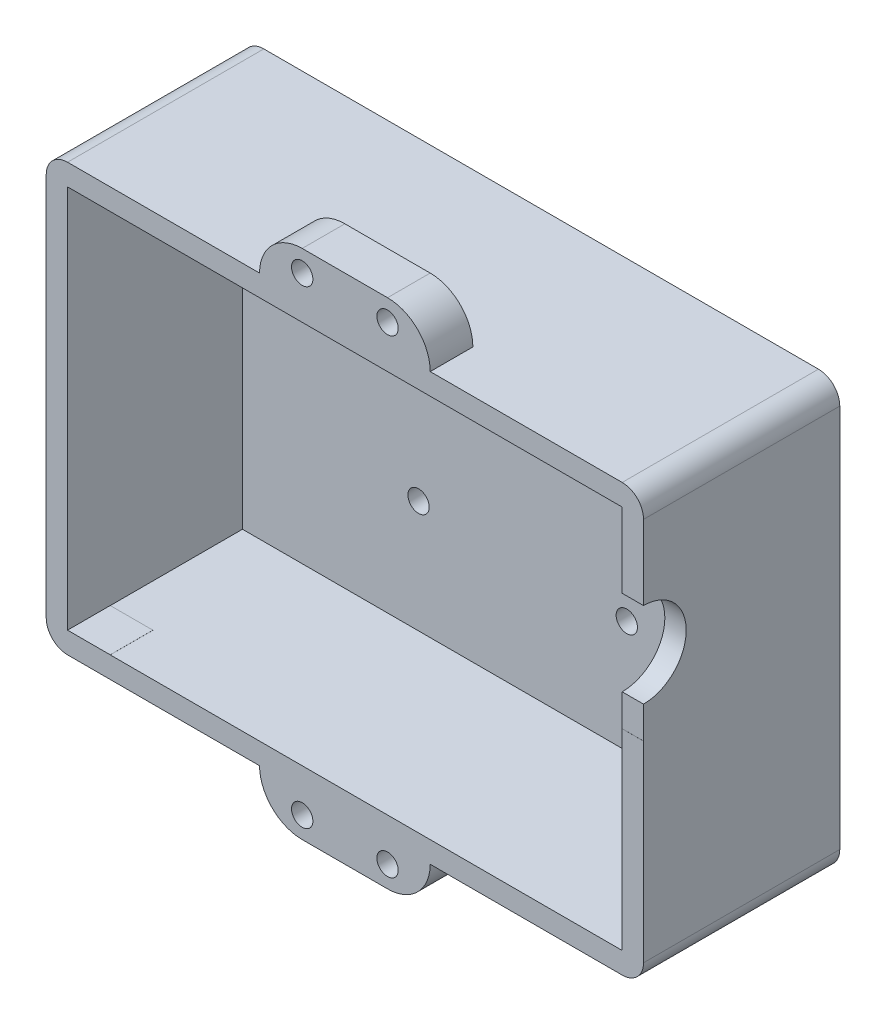
SolidWorks part; units mm, degrees
ref_plane "Front Plane" through (0, 0, 0) normal (0, 0, 1) x (1, 0, 0)
ref_plane "Top Plane" through (0, 0, 0) normal (0, 1, 0) x (1, 0, 0)
ref_plane "Right Plane" through (0, 0, 0) normal (1, 0, 0) x (0, 0, -1)
sketch "Sketch1" plane through (0, 0, 0) normal (0, 0, 1) x (1, 0, 0)
  line L1 (0, 0) -> (76.2, 0)
  line L2 (0, 0) -> (0, -63.5)
  line L3 (0, -63.5) -> (76.2, -63.5)
  line L4 (76.2, 0) -> (76.2, -63.5)
  dimension "D1" = 76.2
  dimension "D2" = 63.5
extrude "Boss-Extrude1" add sketch "Sketch1" along normal blind 31.75
sketch "Sketch2" plane through (0, 0, 31.75) normal (0, 0, 1) x (1, 0, 0)
  line L0 (0, 0) -> (0, -63.5) construction
  line L1 (3.175, -3.175) -> (73.025, -3.175)
  line L2 (3.175, -3.175) -> (3.175, -60.325)
  line L3 (3.175, -60.325) -> (73.025, -60.325)
  line L4 (73.025, -3.175) -> (73.025, -60.325)
  line L5 (76.2, 0) -> (0, 0) construction
  line L6 (76.2, -63.5) -> (76.2, 0) construction
  line L7 (0, -63.5) -> (76.2, -63.5) construction
  dimension "D1" = 3.175
  dimension "D2" = 3.175
  dimension "D3" = 3.175
  dimension "D4" = 3.175
extrude "Cut-Extrude1" cut sketch "Sketch2" against normal blind 28.575
sketch "Sketch3" plane through (0, 0, 0) normal (0, 0, -1) x (-1, 0, 0)
  line L0 (-76.2, 0) -> (0, 0) construction
  line L1 (-47.625, -19.05) -> (-28.575, -19.05)
  line L2 (-47.625, -19.05) -> (-47.625, -44.45)
  line L3 (-47.625, -44.45) -> (-28.575, -44.45)
  line L4 (-28.575, -19.05) -> (-28.575, -44.45)
  line L5 (-76.2, -63.5) -> (-76.2, 0) construction
  point P4 (-38.1, -19.05)
  dimension "D1" = 19.05
  dimension "D2" = 25.4
  dimension "D3" = 19.05
  dimension "D4" = 28.575
extrude "Cut-Extrude2" cut sketch "Sketch3" against normal blind 28.575
sketch "Sketch4" plane through (0, 0, 0) normal (0, 0, -1) x (-1, 0, 0)
  line L0 (-47.625, -19.05) -> (-47.625, -44.45) construction
  line L1 (-28.575, -44.45) -> (-28.575, -19.05) construction
  line L3 (-76.2, 0) -> (0, 0) construction
  line L4 (0, -63.5) -> (-76.2, -63.5) construction
  line L5 (-47.625, -19.05) -> (-47.625, -12.7)
  line L6 (-47.625, -12.7) -> (-28.575, -12.7)
  line L7 (-28.575, -12.7) -> (-28.575, -19.05)
  line L8 (-28.575, -19.05) -> (-47.625, -19.05)
  circle A0 centre (-52.0383, -19.05) radius 1.5875
  circle A1 centre (-24.257, -19.05) radius 1.5875
  circle A2 centre (-52.0382, -44.45) radius 1.5875
  circle A3 centre (-24.257, -44.45) radius 1.5875
  dimension "D1" = 3.175
  dimension "D2" = 27.7812
  dimension "D3" = 4.4132
  dimension "D4" = 4.4132
  dimension "D5" = 27.7812
  dimension "D6" = 4.318
  dimension "D7" = 4.318
  dimension "D8" = 19.05
  dimension "D9" = 19.05
  dimension "D10" = 6.35
extrude "Cut-Extrude3" cut sketch "Sketch4" against normal blind 28.575
sketch "Sketch5" plane through (0, 0, 0) normal (0, 0, -1) x (-1, 0, 0)
  line L0 (-47.625, -44.45) -> (-47.625, -50.8)
  line L1 (-47.625, -50.8) -> (-28.575, -50.8)
  line L2 (-28.575, -50.8) -> (-28.575, -44.45)
  line L3 (-47.625, -44.45) -> (-28.575, -44.45)
  dimension "D1" = 6.35
extrude "Cut-Extrude4" cut sketch "Sketch5" against normal blind 28.575
sketch "Sketch7" plane through (0, 0, 0) normal (0, 1, 0) x (1, 0, 0)
  line L0 (76.2, -31.75) -> (0, -31.75) construction
  line L1 (25.4, -31.75) -> (50.8, -31.75)
  line L2 (25.4, -31.75) -> (25.4, -25.4)
  line L3 (25.4, -25.4) -> (50.8, -25.4)
  line L4 (50.8, -31.75) -> (50.8, -25.4)
  line L5 (0, -31.75) -> (0, 0) construction
  dimension "D1" = 25.4
  dimension "D2" = 6.35
  dimension "D3" = 25.4
extrude "Boss-Extrude2" add sketch "Sketch7" along normal blind 6.35
sketch "Sketch9" plane through (0, 0, 25.4) normal (0, 0, -1) x (-1, 0, 0)
  line L0 (-50.8, 6.35) -> (-50.8, 0) construction
  line L1 (-25.4, 6.35) -> (-25.4, 0) construction
  circle A0 centre (-44.45, 3.175) radius 1.5875
  circle A1 centre (-31.75, 3.175) radius 1.5875
  dimension "D1" = 3.175
  dimension "D2" = 6.35
  dimension "D3" = 6.35
extrude "Cut-Extrude5" cut sketch "Sketch9" against normal blind 6.35
sketch "Sketch10" plane through (0, -63.5, 0) normal (0, -1, 0) x (1, 0, 0)
  line L0 (0, 31.75) -> (76.2, 31.75) construction
  line L1 (25.4, 31.75) -> (50.8, 31.75)
  line L2 (25.4, 31.75) -> (25.4, 25.4)
  line L3 (25.4, 25.4) -> (50.8, 25.4)
  line L4 (50.8, 31.75) -> (50.8, 25.4)
  line L5 (76.2, 31.75) -> (76.2, 0) construction
  dimension "D1" = 25.4
  dimension "D2" = 6.35
  dimension "D3" = 25.4
extrude "Boss-Extrude3" add sketch "Sketch10" along normal blind 6.35
sketch "Sketch11" plane through (0, 0, 25.4) normal (0, 0, -1) x (-1, 0, 0)
  line L0 (-50.8, -69.85) -> (-50.8, -63.5) construction
  line L1 (-25.4, -69.85) -> (-25.4, -63.5) construction
  circle A0 centre (-44.45, -66.675) radius 1.5875
  circle A1 centre (-31.75, -66.675) radius 1.5875
  dimension "D1" = 6.35
  dimension "D2" = 6.35
extrude "Cut-Extrude6" cut sketch "Sketch11" against normal blind 6.35
sketch "Sketch12" plane through (76.2, 0, 0) normal (1, 0, 0) x (0, 0, -1)
  line L1 (-31.75, -63.5) -> (-31.75, 0) construction
  line L2 (-31.75, -63.5) -> (0, -63.5) construction
  circle A1 centre (-31.75, -28.575) radius 6.35
  dimension "D1" = 34.925
  dimension "D2" = 12.7
extrude "Cut-Extrude8" cut sketch "Sketch12" against normal blind 6.35
sketch "Sketch13" plane through (76.2, 0, 0) normal (1, 0, 0) x (0, 0, -1)
  line L1 (-31.75, -22.225) -> (-24.5719, -22.225)
  line L2 (-31.75, -22.225) -> (-31.75, -35.8201)
  line L3 (-31.75, -35.8201) -> (-24.5719, -35.8201)
  line L4 (-24.5719, -22.225) -> (-24.5719, -35.8201)
extrude "Boss-Extrude4" add sketch "Sketch13" against normal blind 3.175
sketch "Sketch14" plane through (76.2, 0, 0) normal (1, 0, 0) x (0, 0, -1)
  line L0 (-31.75, -63.5) -> (-31.75, 0) construction
  line L1 (-25.4, -63.5) -> (-31.75, -63.5) construction
  circle A0 centre (-31.75, -25.4) radius 6.35
  dimension "D1" = 12.7
  dimension "D2" = 38.1
extrude "Cut-Extrude9" cut sketch "Sketch14" against normal blind 3.175
sketch "Sketch15" plane through (0, 0, 0) normal (0, 0, -1) x (-1, 0, 0)
  circle A0 centre (-52.0383, -19.05) radius 1.5875
  circle A1 centre (-24.257, -19.05) radius 1.5875
  circle A2 centre (-24.257, -44.45) radius 1.5875
  circle A3 centre (-52.0382, -44.45) radius 1.5875
sketch "Sketch16" plane through (0, 0, 0) normal (0, 0, -1) x (-1, 0, 0)
  line L0 (-52.0383, -19.05) -> (-52.0383, 0)
  line L1 (-76.2, 0) -> (0, 0) construction
  line L2 (-24.257, -19.05) -> (-24.257, 0)
  line L3 (-52.0382, -44.45) -> (-52.0382, -63.5)
  line L4 (0, -63.5) -> (-76.2, -63.5) construction
  line L5 (-24.257, -44.45) -> (-24.257, -63.5)
  circle A0 centre (-53.6258, -19.05) radius 1.5875
  circle A1 centre (-52.0383, -19.05) radius 1.5875 construction
  circle A2 centre (-53.6257, -44.45) radius 1.5875
  circle A3 centre (-52.0382, -44.45) radius 1.5875 construction
  circle A4 centre (-22.6695, -19.05) radius 1.5875
  circle A5 centre (-24.257, -19.05) radius 1.5875 construction
  circle A6 centre (-22.6695, -44.45) radius 1.5875
  circle A7 centre (-24.257, -44.45) radius 1.5875 construction
  circle M2 centre (-52.0382, -44.45) radius 1.5875
  circle M3 centre (-24.257, -19.05) radius 1.5875
  circle M4 centre (-52.0383, -19.05) radius 1.5875
extrude "Boss-Extrude8" add sketch "Sketch15" against normal blind 3.175
extrude "Cut-Extrude11" cut sketch "Sketch16" against normal blind 8.509 contours A0 M4 | A0 M4 | A4 M3 | A4 M3 | A2 M2 | A2 M2 | A6
sketch "Sketch18" plane through (0, 0, 0) normal (0, 0, -1) x (-1, 0, 0)
  line L0 (-50.1096, -12.7) -> (-47.625, -12.7)
  line L1 (-47.625, -12.7) -> (-26.0904, -12.7)
  line L2 (-47.625, -10.2154) -> (-28.575, -10.2154)
  arc A0 (-47.625, -10.2154) -> (-50.1096, -12.7) centre (-47.625, -12.7) ccw
  arc A1 (-28.575, -10.2154) -> (-26.0904, -12.7) centre (-28.575, -12.7) cw
extrude "Cut-Extrude12" cut sketch "Sketch18" against normal blind 8.509
sketch "Sketch26" plane through (0, 0, 0) normal (0, 0, -1) x (-1, 0, 0)
  line L1 (-76.2, 0) -> (0, 0) construction
  line L2 (0, -63.5) -> (-76.2, -63.5) construction
  line L3 (0, 0) -> (0, -63.5) construction
  line L4 (-76.2, -63.5) -> (-76.2, 0) construction
  circle A0 centre (-68.58, -31.75) radius 2.921
  circle A1 centre (-64.77, -25.4) radius 2.921
  circle A2 centre (-60.96, -19.05) radius 2.921
  circle A3 centre (-64.77, -38.1) radius 2.921
  circle A4 centre (-60.96, -44.45) radius 2.921
  circle A5 centre (-7.62, -31.75) radius 2.921
  circle A6 centre (-11.43, -25.4) radius 2.921
  circle A7 centre (-15.24, -19.05) radius 2.921
  circle A8 centre (-11.43, -38.1) radius 2.921
  circle A9 centre (-15.24, -44.45) radius 2.921
  dimension "D3" = 7.62
  dimension "D4" = 11.43
  dimension "D5" = 15.24
  dimension "D6" = 11.43
  dimension "D7" = 15.24
  dimension "D12" = 7.62
  dimension "D13" = 11.43
  dimension "D14" = 11.43
  dimension "D15" = 15.24
  dimension "D16" = 15.24
  dimension "D17" = 31.75
  dimension "D18" = 25.4
  dimension "D19" = 19.05
  dimension "D20" = 25.4
  dimension "D21" = 19.05
extrude "Cut-Extrude24" cut sketch "Sketch26" against normal blind 72.898
sketch "Sketch32" plane through (0, 0, 3.175) normal (0, 0, 1) x (1, 0, 0)
  line L1 (3.175, -3.175) -> (73.025, -3.175)
  line L2 (3.175, -3.175) -> (3.175, -60.325)
  line L3 (3.175, -60.325) -> (73.025, -60.325)
  line L4 (73.025, -3.175) -> (73.025, -60.325)
  circle A0 centre (15.24, -19.05) radius 2.921
  circle A1 centre (11.43, -25.4) radius 2.921
  circle A2 centre (7.62, -31.75) radius 2.921
  circle A3 centre (11.43, -38.1) radius 2.921
  circle A4 centre (15.24, -44.45) radius 2.921
  circle A5 centre (60.96, -44.45) radius 2.921
  circle A6 centre (64.77, -38.1) radius 2.921
  circle A7 centre (68.58, -31.75) radius 2.921
  circle A8 centre (64.77, -25.4) radius 2.921
  circle A9 centre (60.96, -19.05) radius 2.921
extrude "Boss-Extrude10" add sketch "Sketch32" along normal blind 5.715
sketch "Sketch36" plane through (0, 0, 0) normal (0, 0, -1) x (-1, 0, 0)
  line L1 (-55.2133, -17.4625) -> (-21.082, -17.4625)
  line L2 (-55.2133, -17.4625) -> (-55.2133, -46.0375)
  line L3 (-55.2133, -46.0375) -> (-21.082, -46.0375)
  line L4 (-21.082, -17.4625) -> (-21.082, -46.0375)
extrude "Cut-Extrude27" cut sketch "Sketch36" against normal blind 38.227 contours L2 L1 L4 L3
sketch "Sketch38" plane through (0, 0, 0) normal (0, 0, -1) x (-1, 0, 0)
  line L0 (-55.2133, -46.0375) -> (-21.082, -46.0375)
  spline S0 degree 3 poles (-55.2133, -46.0375) (-46.3247, -54.6455) (-29.9359, -54.7487) (-21.082, -46.0375) knots 0 0 0 0 1 1 1 1
extrude "Cut-Extrude29" cut sketch "Sketch38" against normal blind 38.227
sketch "Sketch39" plane through (0, 0, 8.89) normal (0, 0, 1) x (1, 0, 0)
  line L0 (3.175, -60.325) -> (73.025, -60.325) construction
  line L1 (3.175, -3.175) -> (21.082, -3.175)
  line L2 (3.175, -3.175) -> (3.175, -60.325)
  line L3 (3.175, -60.325) -> (21.082, -60.325)
  line L4 (21.082, -3.175) -> (21.082, -60.325)
  line L6 (73.025, -3.175) -> (55.2132, -3.175)
  line L7 (73.025, -3.175) -> (73.025, -60.325)
  line L8 (73.025, -60.325) -> (55.2132, -60.325)
  line L9 (55.2132, -3.175) -> (55.2132, -60.325)
  circle A0 centre (15.24, -19.05) radius 1.905
  circle A1 centre (11.43, -25.4) radius 1.905
  circle A2 centre (7.62, -31.75) radius 1.905
  circle A3 centre (11.43, -38.1) radius 1.905
  circle A4 centre (15.24, -44.45) radius 1.905
  circle A5 centre (60.96, -44.45) radius 1.905
  circle A6 centre (64.77, -38.1) radius 1.905
  circle A7 centre (68.58, -31.75) radius 1.905
  circle A8 centre (64.77, -25.4) radius 1.905
  circle A9 centre (60.96, -19.05) radius 1.905
  dimension "D1" = 3.81
extrude "Boss-Extrude11" add sketch "Sketch39" along normal blind 2.54
sketch "Sketch44" plane through (0, 0, 0) normal (0, 0, -1) x (-1, 0, 0)
  line L0 (-28.575, -12.7) -> (-28.575, -17.4625) construction
  line L1 (-28.575, -17.4625) -> (-47.625, -17.4625) construction
  line L2 (-47.625, -9.8743) -> (-28.575, -9.9695)
  line L3 (-21.082, -17.4625) -> (-55.2133, -17.4625)
  arc A0 (-55.2133, -17.4625) -> (-47.625, -9.8743) centre (-47.625, -17.4625) cw
  arc A1 (-21.082, -17.4625) -> (-28.575, -9.9695) centre (-28.575, -17.4625) ccw
extrude "Cut-Extrude34" cut sketch "Sketch44" against normal blind 11.176
sketch "Sketch47" plane through (0, 0, 0) normal (0, 0, -1) x (-1, 0, 0)
  line L0 (-76.2, 0) -> (0, 0) construction
  line L1 (-55.372, -9.144) -> (-20.828, -9.144)
  line L2 (-55.372, -9.144) -> (-55.372, -54.356)
  line L3 (-55.372, -54.356) -> (-20.828, -54.356)
  line L4 (-20.828, -9.144) -> (-20.828, -54.356)
  line L5 (-76.2, -63.5) -> (-76.2, 0) construction
  line L6 (-44.0174, -9.144) -> (-55.372, -9.144)
  line L7 (-55.372, -44.45) -> (-55.372, -54.356)
  line L8 (-32.3914, -54.356) -> (-20.828, -54.356)
  line L9 (-32.3914, -9.144) -> (-20.828, -9.144)
  spline S0 degree 2 poles (-55.372, -19.05) (-51.6624, -8.9987) (-44.0174, -9.144) knots 0 0 0 1 1 1
  spline S1 degree 2 poles (-20.828, -19.05) (-24.615, -8.9285) (-32.3914, -9.144) knots 0 0 0 1 1 1
  spline S2 degree 2 poles (-55.372, -44.45) (-51.6624, -54.5013) (-44.0174, -54.356) knots 0 0 0 1 1 1
  spline S3 degree 2 poles (-20.828, -44.45) (-24.615, -54.5715) (-32.3914, -54.356) knots 0 0 0 1 1 1
  point P4 (-55.372, -31.75)
  point P7 (-38.1, -9.144)
  dimension "D1" = 34.544
  dimension "D2" = 45.212
  dimension "D3" = 31.75
  dimension "D4" = 38.1
extrude "Cut-Extrude36" cut sketch "Sketch47" against normal blind 11.43 contours L2 L1 L4 L3
sketch "Sketch51" plane through (76.2, 0, 0) normal (1, 0, 0) x (0, 0, -1)
  line L1 (0, 0) -> (-31.75, 0)
  line L2 (0, 0) -> (0, -63.5)
  line L3 (0, -63.5) -> (-31.75, -63.5)
  line L4 (-31.75, 0) -> (-31.75, -63.5)
extrude "Boss-Extrude16" add sketch "Sketch51" along normal blind 6.35
sketch "Sketch52" plane through (0, 0, 0) normal (-1, 0, 0) x (0, 0, 1)
  line L1 (0, 0) -> (31.75, 0)
  line L2 (0, 0) -> (0, -63.5)
  line L3 (0, -63.5) -> (31.75, -63.5)
  line L4 (31.75, 0) -> (31.75, -63.5)
extrude "Boss-Extrude17" add sketch "Sketch52" along normal blind 6.35
sketch "Sketch53" plane through (76.2, 0, 0) normal (-1, 0, 0) x (0, 0, 1)
  line L0 (31.75, -19.05) -> (31.75, -31.75) construction
  circle A0 centre (31.75, -25.4) radius 6.35
extrude "Cut-Extrude37" cut sketch "Sketch53" against normal blind 6.35
sketch "Sketch54" plane through (0, 0, 31.75) normal (0, 0, 1) x (1, 0, 0)
  line L1 (3.175, -3.175) -> (-3.175, -3.175)
  line L2 (3.175, -3.175) -> (3.175, -60.1885)
  line L3 (3.175, -60.1885) -> (-3.175, -60.1885)
  line L4 (-3.175, -3.175) -> (-3.175, -60.1885)
  line L5 (73.025, -3.175) -> (79.375, -3.175)
  line L6 (73.025, -3.175) -> (73.025, -60.325)
  line L7 (73.025, -60.325) -> (79.375, -60.325)
  line L8 (79.375, -3.175) -> (79.375, -60.325)
  dimension "D1" = 6.35
  dimension "D2" = 6.35
extrude "Cut-Extrude38" cut sketch "Sketch54" against normal blind 21.59
sketch "Sketch57" plane through (0, 0, 10.16) normal (0, 0, 1) x (1, 0, 0)
  line L1 (-3.175, -3.175) -> (3.175, -3.175)
  line L2 (-3.175, -3.175) -> (-3.175, -60.325)
  line L3 (-3.175, -60.325) -> (3.175, -60.325)
  line L4 (3.175, -3.175) -> (3.175, -60.325)
  line L5 (73.025, -60.325) -> (79.375, -60.325)
  line L6 (73.025, -60.325) -> (73.025, -3.175)
  line L7 (73.025, -3.175) -> (79.375, -3.175)
  line L8 (79.375, -60.325) -> (79.375, -3.175)
extrude "Boss-Extrude20" add sketch "Sketch57" along normal blind 1.27
sketch "Sketch59" plane through (0, 0, 0) normal (0, 0, -1) x (-1, 0, 0)
  line L1 (-56.5485, -13.4059) -> (-73.3958, -13.4059)
  line L2 (-56.5485, -13.4059) -> (-56.5485, -49.4675)
  line L3 (-56.5485, -49.4675) -> (-73.3958, -49.4675)
  line L4 (-73.3958, -13.4059) -> (-73.3958, -49.4675)
  line L5 (-19.1642, -12.2921) -> (-2.4561, -12.2921)
  line L6 (-19.1642, -12.2921) -> (-19.1642, -48.9106)
  line L7 (-19.1642, -48.9106) -> (-2.4561, -48.9106)
  line L8 (-2.4561, -12.2921) -> (-2.4561, -48.9106)
extrude "Boss-Extrude21" add sketch "Sketch59" against normal blind 11.43
sketch "Sketch61" plane through (0, 0, 0) normal (0, 0, -1) x (-1, 0, 0)
  line L0 (-82.55, -63.5) -> (-82.55, 0) construction
  line L1 (-82.55, 0) -> (6.35, 0) construction
  line L2 (6.35, -63.5) -> (-82.55, -63.5) construction
  line L3 (6.35, 0) -> (6.35, -63.5) construction
  circle A0 centre (-74.93, -31.75) radius 2.921
  circle A1 centre (-71.12, -25.4) radius 2.921
  circle A2 centre (73.7439, -27.6774) radius 2.921
  circle A3 centre (-67.31, -19.05) radius 2.921
  circle A4 centre (-71.12, -38.1) radius 2.921
  circle A5 centre (-67.31, -44.45) radius 2.921
  circle A6 centre (-1.27, -31.75) radius 2.921
  circle A7 centre (-5.08, -25.4) radius 2.921
  circle A8 centre (-8.89, -19.05) radius 2.921
  circle A9 centre (-5.08, -38.1) radius 2.921
  circle A10 centre (-8.89, -44.45) radius 2.921
  dimension "D1" = 7.62
  dimension "D2" = 11.43
  dimension "D3" = 11.43
  dimension "D4" = 15.24
  dimension "D5" = 15.24
  dimension "D6" = 31.75
  dimension "D7" = 25.4
  dimension "D8" = 25.4
  dimension "D9" = 19.05
  dimension "D10" = 19.05
  dimension "D11" = 7.62
  dimension "D12" = 31.75
  dimension "D13" = 11.43
  dimension "D14" = 25.4
  dimension "D15" = 19.05
  dimension "D16" = 15.24
  dimension "D17" = 11.43
  dimension "D18" = 25.4
  dimension "D19" = 15.24
  dimension "D20" = 19.05
extrude "Cut-Extrude39" cut sketch "Sketch61" against normal blind 8.89
sketch "Sketch62" plane through (0, 0, 8.89) normal (0, 0, -1) x (-1, 0, 0)
  circle A0 centre (-67.31, -19.05) radius 1.905
  circle A1 centre (-71.12, -25.4) radius 1.905
  circle A2 centre (-74.93, -31.75) radius 1.905
  circle A3 centre (-71.12, -38.1) radius 1.905
  circle A4 centre (-67.31, -44.45) radius 1.905
  circle A5 centre (-8.89, -44.45) radius 1.905
  circle A6 centre (-5.08, -38.1) radius 1.905
  circle A7 centre (-1.27, -31.75) radius 1.905
  circle A8 centre (-5.08, -25.4) radius 1.905
  circle A9 centre (-8.89, -19.05) radius 1.905
  dimension "D1" = 3.81
extrude "Cut-Extrude40" cut sketch "Sketch62" against normal blind 2.54
sketch "Sketch63" plane through (-3.175, 0, 0) normal (1, 0, 0) x (0, 0, -1)
  line L6 (-11.43, -3.175) -> (-31.75, -3.175) construction
  line L7 (-20.32, -3.175) -> (-21.59, -3.175)
  line L8 (-20.32, -3.175) -> (-20.32, -60.1885)
  line L9 (-20.32, -60.1885) -> (-21.59, -60.1885)
  line L10 (-21.59, -3.175) -> (-21.59, -60.1885)
  line L11 (-11.43, -60.1885) -> (-31.75, -60.1885) construction
  line L12 (-11.43, -3.175) -> (-11.43, -60.1885) construction
  line L14 (-21.59, -3.175) -> (-25.4, -3.175)
  line L15 (-21.59, -3.175) -> (-21.59, -60.1885)
  line L16 (-21.59, -60.1885) -> (-25.4, -60.1885)
  line L17 (-25.4, -3.175) -> (-25.4, -60.1885)
  dimension "D1" = 8.89
  dimension "D2" = 1.27
  dimension "D3" = 3.81
sketch "Sketch64" plane through (0, -60.1885, 0) normal (0, 1, 0) x (1, 0, 0)
  line L1 (-3.175, -11.43) -> (3.175, -11.43)
  line L2 (-3.175, -11.43) -> (-3.175, -31.75)
  line L3 (-3.175, -31.75) -> (3.175, -31.75)
  line L4 (3.175, -11.43) -> (3.175, -31.75)
extrude "Cut-Extrude42" cut sketch "Sketch64" against normal blind 0.127
extrude "Boss-Extrude22" add sketch "Sketch63" along normal blind 83.439 contours L8 L7 L10 L9 | L15 L14 L17 L16
sketch "Sketch65" plane through (0, 0, 0) normal (0, 0, -1) x (-1, 0, 0)
  line L0 (-82.55, 0) -> (6.35, 0) construction
  line L1 (6.35, 0) -> (6.35, -63.5) construction
  line L2 (-82.55, -63.5) -> (-82.55, 0) construction
  circle A0 centre (-53.594, -19.05) radius 1.5875
  circle A1 centre (-22.606, -19.05) radius 1.5875
  circle A2 centre (-22.606, -44.45) radius 1.5875
  circle A3 centre (-53.594, -44.45) radius 1.5875
  dimension "D1" = 3.175
  dimension "D2" = 25.4
  dimension "D3" = 25.4
  dimension "D4" = 19.05
  dimension "D5" = 19.05
  dimension "D6" = 28.956
  dimension "D7" = 28.956
  dimension "D8" = 28.956
  dimension "D9" = 28.956
extrude "Cut-Extrude43" cut sketch "Sketch65" against normal blind 83.439
sketch "Sketch66" plane through (0, 0, 20.32) normal (0, 0, -1) x (-1, 0, 0)
  line L0 (-82.55, -63.5) -> (-82.55, 0) construction
  line L1 (-50.8, -12.7) -> (-25.4, -12.7)
  line L2 (-50.8, -12.7) -> (-50.8, -50.8)
  line L3 (-50.8, -50.8) -> (-25.4, -50.8)
  line L4 (-25.4, -12.7) -> (-25.4, -50.8)
  line L5 (-82.55, 0) -> (6.35, 0) construction
  point P4 (-50.8, -31.75)
  point P6 (-38.1, -12.7)
  dimension "D3" = 44.45
  dimension "D1" = 25.4
  dimension "D2" = 38.1
  dimension "D4" = 31.75
extrude "Cut-Extrude44" cut sketch "Sketch66" against normal blind 83.439
sketch "Sketch67" plane through (0, 0, 0) normal (0, 0, -1) x (-1, 0, 0)
  line L0 (-55.372, -9.144) -> (-55.372, -54.356) construction
  line L1 (-55.372, -9.144) -> (-20.828, -9.144) construction
  line L2 (-20.828, -9.144) -> (-20.828, -54.356) construction
  line L3 (-55.372, -54.356) -> (-20.828, -54.356) construction
  line L4 (-53.6737, -9.144) -> (-55.372, -9.144)
  line L5 (-55.372, -9.144) -> (-55.372, -12.7)
  line L6 (-55.372, -50.8) -> (-55.372, -54.356)
  line L7 (-55.372, -54.356) -> (-53.6737, -54.356)
  line L8 (-22.5263, -54.356) -> (-20.828, -54.356)
  line L9 (-20.828, -54.356) -> (-20.828, -50.8)
  line L10 (-20.828, -12.7) -> (-20.828, -9.144)
  line L11 (-20.828, -9.144) -> (-22.5263, -9.144)
  arc A0 (-55.372, -12.7) -> (-53.6737, -9.144) centre (-50.8, -12.7) cw
  arc A1 (-20.828, -12.7) -> (-22.5263, -9.144) centre (-25.4, -12.7) ccw
  arc A2 (-20.828, -50.8) -> (-22.5263, -54.356) centre (-25.4, -50.8) cw
  arc A3 (-55.372, -50.8) -> (-53.6737, -54.356) centre (-50.8, -50.8) ccw
extrude "Boss-Extrude23" add sketch "Sketch67" against normal blind 11.43
sketch "Sketch68" plane through (0, 0, 20.32) normal (0, 0, -1) x (-1, 0, 0)
  line L0 (-67.31, -17.145) -> (-65.405, -19.05)
  line L1 (-65.405, -19.05) -> (-73.025, -31.75)
  line L2 (-73.025, -31.75) -> (-65.405, -44.45)
  line L3 (-65.405, -44.45) -> (-67.31, -46.355)
  line L4 (-67.31, -46.355) -> (-76.835, -31.75)
  line L5 (-76.835, -31.75) -> (-67.31, -17.145)
  line L6 (-10.795, -19.05) -> (-8.89, -17.145)
  line L7 (-8.89, -17.145) -> (0.635, -31.75)
  line L8 (0.635, -31.75) -> (-8.89, -46.355)
  line L9 (-8.89, -46.355) -> (-10.795, -44.45)
  line L10 (-10.795, -44.45) -> (-3.175, -31.75)
  line L11 (-3.175, -31.75) -> (-10.795, -19.05)
  circle A0 centre (-67.31, -19.05) radius 1.905 construction
  circle A1 centre (-74.93, -31.75) radius 1.905 construction
  circle A2 centre (-67.31, -44.45) radius 1.905 construction
  circle A3 centre (-8.89, -19.05) radius 1.905 construction
  circle A4 centre (-1.27, -31.75) radius 1.905 construction
  circle A5 centre (-8.89, -44.45) radius 1.905 construction
extrude "Cut-Extrude45" cut sketch "Sketch68" against normal blind 11.43
sketch "Sketch71" plane through (0, 0, 31.75) normal (0, 0, 1) x (1, 0, 0)
  line L0 (25.4, 0) -> (-6.35, 0) construction
  line L1 (-6.35, -63.5) -> (-6.35, 0) construction
  line L2 (82.55, 0) -> (50.8, 0) construction
  line L3 (82.55, 0) -> (82.55, -19.05) construction
  line L4 (82.55, -31.75) -> (82.55, -63.5) construction
  line L5 (50.8, -63.5) -> (82.55, -63.5) construction
  line L6 (-3.175, 0) -> (-6.35, 0)
  line L7 (-6.35, 0) -> (-6.35, -3.175)
  line L8 (-6.35, -60.3155) -> (-6.35, -63.5)
  line L9 (-6.35, -63.5) -> (-3.175, -63.4905)
  line L10 (82.55, -60.325) -> (82.55, -63.5)
  line L11 (82.55, -63.5) -> (79.375, -63.5)
  line L12 (79.375, 0) -> (82.55, 0)
  line L13 (82.55, 0) -> (82.55, -3.175)
  arc A0 (-3.175, 0) -> (-6.35, -3.175) centre (-3.175, -3.175) ccw
  arc A1 (79.375, 0) -> (82.55, -3.175) centre (79.375, -3.175) cw
  arc A2 (82.55, -60.325) -> (79.375, -63.5) centre (79.375, -60.325) cw
  arc A3 (-6.35, -60.3155) -> (-3.175, -63.4905) centre (-3.175, -60.3155) ccw
extrude "Cut-Extrude47" cut sketch "Sketch71" against normal blind 63.5
sketch "Sketch72" plane through (-3.175, 0, 0) normal (1, 0, 0) x (0, 0, -1)
  circle A0 centre (-31.75, -25.4) radius 6.35
extrude "Cut-Extrude48" cut sketch "Sketch72" against normal blind 63.5
sketch "Sketch73" plane through (82.55, 0, 0) normal (1, 0, 0) x (0, 0, -1)
  line L0 (-31.75, -3.175) -> (-31.75, -19.05) construction
  line L1 (-31.75, -19.05) -> (-23.8556, -19.05)
  line L2 (-31.75, -19.05) -> (-31.75, -31.75)
  line L3 (-31.75, -31.75) -> (-23.8556, -31.75)
  line L4 (-23.8556, -19.05) -> (-23.8556, -31.75)
  arc A0 (-31.75, -31.75) -> (-31.75, -19.05) centre (-31.75, -25.4) ccw construction
extrude "Boss-Extrude24" add sketch "Sketch73" against normal blind 3.175
sketch "Sketch74" plane through (0, 0, 25.4) normal (0, 0, -1) x (-1, 0, 0)
  line L0 (-50.8, 0) -> (-25.4, 0) construction
  line L5 (-44.45, 6.35) -> (-50.8, 6.35)
  line L10 (-50.8, 6.35) -> (-50.8, 0)
  line L11 (-31.75, 6.35) -> (-25.4, 6.35)
  line L12 (-25.4, 6.35) -> (-25.4, 0)
  arc A0 (-44.45, 6.35) -> (-50.8, 0) centre (-44.45, 0) ccw
  arc A1 (-31.75, 6.35) -> (-25.4, 0) centre (-31.75, 0) cw
extrude "Cut-Extrude49" cut sketch "Sketch74" against normal blind 9.779
sketch "Sketch75" plane through (0, 0, 25.4) normal (0, 0, -1) x (-1, 0, 0)
  line L0 (6.35, -63.5) -> (-79.375, -63.5) construction
  line L5 (-25.4, -63.5) -> (-50.8, -63.5) construction
  line L10 (-50.8, -63.5) -> (-50.8, -69.85)
  line L11 (-50.8, -69.85) -> (-44.45, -69.85)
  line L12 (-31.75, -69.85) -> (-25.4, -69.85)
  line L13 (-25.4, -69.85) -> (-25.4, -63.5)
  arc A0 (-50.8, -63.5) -> (-44.45, -69.85) centre (-44.45, -63.5) ccw
  arc A1 (-25.4, -63.5) -> (-31.75, -69.85) centre (-31.75, -63.5) cw
  dimension "D1" = 6.35
  dimension "D2" = 6.35
extrude "Cut-Extrude50" cut sketch "Sketch75" against normal blind 9.779
sketch "Sketch76" plane through (0, 0, 20.32) normal (0, 0, -1) x (-1, 0, 0)
  line L0 (-67.31, -16.129) -> (-64.389, -19.05)
  line L1 (-64.389, -19.05) -> (-72.009, -31.75)
  line L2 (-72.009, -31.75) -> (-64.389, -44.45)
  line L3 (-64.389, -44.45) -> (-67.31, -47.371)
  line L4 (-67.31, -47.371) -> (-77.851, -31.75)
  line L5 (-77.851, -31.75) -> (-67.31, -16.129)
  line L6 (-11.811, -19.05) -> (-8.89, -16.129)
  line L7 (-8.89, -16.129) -> (1.651, -31.75)
  line L8 (1.651, -31.75) -> (-7.5154, -47.0274)
  line L9 (-7.5154, -47.0274) -> (-11.811, -44.45)
  line L10 (-11.811, -44.45) -> (-4.191, -31.75)
  line L11 (-4.191, -31.75) -> (-11.811, -19.05)
  circle A0 centre (-67.31, -19.05) radius 2.921 construction
  circle A1 centre (-67.31, -19.05) radius 2.921 construction
  circle A2 centre (-74.93, -31.75) radius 2.921 construction
  circle A3 centre (-74.93, -31.75) radius 2.921 construction
  circle A4 centre (-67.31, -44.45) radius 2.921 construction
  circle A5 centre (-67.31, -44.45) radius 2.921 construction
  circle A6 centre (-8.89, -19.05) radius 2.921 construction
  circle A7 centre (-8.89, -19.05) radius 2.921 construction
  circle A8 centre (-1.27, -31.75) radius 2.921 construction
  circle A9 centre (-1.27, -31.75) radius 2.921 construction
  circle A10 centre (-8.89, -44.45) radius 2.921 construction
  circle A11 centre (-8.89, -44.45) radius 2.921 construction
extrude "Cut-Extrude51" cut sketch "Sketch76" against normal blind 9.779
sketch "Sketch81" plane through (0, 0, 31.75) normal (0, 0, 1) x (1, 0, 0)
  line L1 (-3.175, -63.4905) -> (-6.4183, -63.4905)
  line L2 (-3.175, -63.4905) -> (-3.175, -63.525)
  line L3 (-3.175, -63.525) -> (-6.4183, -63.525)
  line L4 (-6.4183, -63.4905) -> (-6.4183, -63.525)
extrude "Cut-Extrude52" cut sketch "Sketch81" against normal blind 36.703
sketch "Sketch85" plane through (0, 0, 0) normal (0, 0, -1) x (-1, 0, 0)
  circle A0 centre (-67.31, -19.05) radius 2.921
  circle A1 centre (-71.12, -25.4) radius 2.921
  circle A2 centre (-74.93, -31.75) radius 2.921
  circle A3 centre (-71.12, -38.1) radius 2.921
  circle A4 centre (-67.31, -44.45) radius 2.921
  circle A5 centre (-8.89, -44.45) radius 2.921
  circle A6 centre (-5.08, -38.1) radius 2.921
  circle A7 centre (-1.27, -31.75) radius 2.921
  circle A8 centre (-5.08, -25.4) radius 2.921
  circle A9 centre (-8.89, -19.05) radius 2.921
extrude "Cut-Extrude53" cut sketch "Sketch85" against normal blind 11.43
sketch "Sketch86" plane through (0, 0, 11.43) normal (0, 0, 1) x (1, 0, 0)
  line L1 (-3.175, -3.175) -> (79.375, -3.175)
  line L2 (-3.175, -3.175) -> (-3.175, -60.325)
  line L3 (-3.175, -60.325) -> (79.375, -60.325)
  line L4 (79.375, -3.175) -> (79.375, -60.325)
  circle A0 centre (5.08, -25.4) radius 1.905
  circle A1 centre (8.89, -19.05) radius 1.905
  circle A2 centre (1.27, -31.75) radius 1.905
  circle A3 centre (5.08, -38.1) radius 1.905
  circle A4 centre (8.89, -44.45) radius 1.905
  circle A5 centre (67.31, -19.05) radius 1.905
  circle A6 centre (71.12, -25.4) radius 1.905
  circle A7 centre (74.93, -31.75) radius 1.905
  circle A8 centre (71.12, -38.1) radius 1.905
  circle A9 centre (67.31, -44.45) radius 1.905
  dimension "D1" = 3.81
extrude "Boss-Extrude28" add sketch "Sketch86" along normal blind 2.54
sketch "Sketch87" plane through (0, 0, 25.4) normal (0, 0, 1) x (1, 0, 0)
  line L0 (25.4, -12.7) -> (50.8, -12.7) construction
  line L1 (25.4698, -12.7) -> (50.8, -12.7)
  line L2 (25.4698, -12.7) -> (25.4698, -50.8)
  line L3 (25.4698, -50.8) -> (50.8, -50.8)
  line L4 (50.8, -12.7) -> (50.8, -50.8)
  circle A0 centre (22.606, -19.05) radius 1.5875
  circle A1 centre (53.594, -19.05) radius 1.5875
  circle A2 centre (53.594, -44.45) radius 1.5875
  circle A3 centre (22.606, -44.45) radius 1.5875
extrude "Cut-Extrude54" cut sketch "Sketch87" against normal blind 38.862
sketch "Sketch88" plane through (0, 0, 11.43) normal (0, 0, -1) x (-1, 0, 0)
  line L1 (-55.372, -12.7) -> (-20.828, -12.7)
  line L2 (-55.372, -12.7) -> (-55.372, -50.8)
  line L3 (-55.372, -50.8) -> (-20.828, -50.8)
  line L4 (-20.828, -12.7) -> (-20.828, -50.8)
  line L5 (-53.6737, -9.144) -> (-22.5263, -9.144)
  line L6 (-53.6737, -9.144) -> (-53.6737, -12.7)
  line L7 (-53.6737, -12.7) -> (-22.5263, -12.7)
  line L8 (-22.5263, -9.144) -> (-22.5263, -12.7)
  line L9 (-53.6737, -54.356) -> (-22.5263, -54.356)
  line L10 (-53.6737, -54.356) -> (-53.6737, -50.8)
  line L11 (-53.6737, -50.8) -> (-22.5263, -50.8)
  line L12 (-22.5263, -54.356) -> (-22.5263, -50.8)
  arc A0 (-55.372, -12.7) -> (-53.6737, -9.144) centre (-50.8, -12.7) cw
  arc A1 (-20.828, -12.7) -> (-22.4774, -9.1515) centre (-25.4698, -12.7) ccw
  arc A2 (-20.828, -50.8) -> (-22.5529, -54.4108) centre (-25.4698, -50.8) cw
  arc A3 (-55.372, -50.8) -> (-53.6737, -54.356) centre (-50.8, -50.8) ccw
  arc A4 (-55.372, -50.8) -> (-53.6737, -54.356) centre (-50.8, -50.8) ccw construction
extrude "Cut-Extrude55" cut sketch "Sketch88" against normal blind 2.54 contours L6 L5 L8 L7 | L2 L1 L4 L3 | L10 L9 L12 L11
sketch "Sketch89" plane through (0, 0, 11.43) normal (0, 0, -1) x (-1, 0, 0)
  line L0 (-53.6737, -9.144) -> (-53.6737, -12.7) construction
  line L1 (-53.6737, -9.144) -> (-22.5263, -9.144)
  line L2 (-20.828, -50.8) -> (-20.828, -12.7)
  line L3 (-55.372, -12.7) -> (-55.372, -50.8)
  line L4 (-53.6737, -54.356) -> (-22.5263, -54.356)
  arc A0 (-55.372, -12.7) -> (-53.6737, -9.144) centre (-50.8, -12.7) cw
  arc A1 (-20.828, -12.7) -> (-22.5263, -9.144) centre (-25.4, -12.7) ccw
  arc A2 (-20.828, -12.7) -> (-22.5263, -9.144) centre (-25.4, -12.7) ccw construction
  arc A3 (-20.828, -50.8) -> (-22.5263, -54.356) centre (-25.4, -50.8) cw
  arc A4 (-22.5263, -54.356) -> (-20.828, -50.8) centre (-25.4, -50.8) ccw construction
  arc A5 (-55.372, -50.8) -> (-53.6737, -54.356) centre (-50.8, -50.8) ccw
  arc A6 (-55.372, -50.8) -> (-53.6737, -54.356) centre (-50.8, -50.8) ccw construction
extrude "Cut-Extrude56" cut sketch "Sketch89" against normal blind 2.54
sketch "Sketch90" plane through (0, 0, 0) normal (0, 0, -1) x (-1, 0, 0)
  line L0 (-80.8542, -31.75) -> (-67.7643, -9.9334)
  line L1 (-80.8542, -31.75) -> (-67.422, -54.1371)
  line L2 (-67.7643, -9.9334) -> (-59.0521, -15.1607)
  line L3 (-67.422, -54.1371) -> (-58.7098, -48.9099)
  line L4 (-58.7098, -48.9099) -> (-69.0058, -31.75)
  line L5 (-69.0058, -31.75) -> (-59.0521, -15.1607)
  line L6 (-8.4868, -9.8483) -> (4.6542, -31.75)
  line L7 (-17.1565, -15.1462) -> (-7.1942, -31.75)
  line L8 (4.6542, -31.75) -> (-8.7009, -54.0086)
  line L9 (-7.1942, -31.75) -> (-17.225, -48.4679)
  line L10 (-8.4868, -9.8483) -> (-17.1565, -15.1462)
  line L11 (-17.225, -48.4679) -> (-8.7009, -54.0086)
  circle A2 centre (-67.31, -19.05) radius 2.921 construction
  circle A4 centre (-71.12, -25.4) radius 2.921 construction
  circle A5 centre (-74.93, -31.75) radius 2.921 construction
  circle A6 centre (-71.12, -38.1) radius 2.921 construction
  circle A7 centre (-67.31, -44.45) radius 2.921 construction
  circle A8 centre (-1.27, -31.75) radius 2.921 construction
  circle A9 centre (-5.08, -25.4) radius 2.921 construction
  circle A10 centre (-8.89, -19.05) radius 2.921 construction
  circle A11 centre (-1.27, -31.75) radius 2.921 construction
  circle A12 centre (-5.08, -38.1) radius 2.921 construction
  circle A13 centre (-8.89, -44.45) radius 2.921 construction
  circle A14 centre (-71.12, -38.1) radius 2.921 construction
  dimension "D1" = 5.08
  dimension "D2" = 5.08
  dimension "D3" = 5.08
  dimension "D4" = 5.08
  dimension "D5" = 5.08
  dimension "D6" = 5.08
  dimension "D8" = 5.08
  dimension "D9" = 5.08
  dimension "D10" = 5.08
  dimension "D11" = 5.08
  dimension "D12" = 5.08
  dimension "D13" = 5.08
  dimension "D14" = 5.08
  dimension "D15" = 5.08
  dimension "D16" = 5.08
  dimension "D17" = 5.08
  dimension "D18" = 5.08
  dimension "D19" = 5.08
  dimension "D20" = 5.08
  dimension "D21" = 5.08
  dimension "D22" = 25.4423
  dimension "D7" = 10.16
  dimension "D23" = 26.1077
  dimension "D24" = 25.5416
  dimension "D25" = 25.9578
  dimension "D26" = 19.4963
  dimension "D27" = 19.3631
  dimension "D28" = 19.3463
  dimension "D29" = 20.0117
  dimension "D30" = 10.1603
extrude "Cut-Extrude57" cut sketch "Sketch90" against normal blind 2.54
sketch "Sketch92" plane through (0, 0, 25.4) normal (0, 0, 1) x (1, 0, 0)
  line L0 (8.89, -16.129) -> (-1.651, -31.75)
  line L1 (-1.651, -31.75) -> (7.5154, -47.0274)
  line L2 (7.5154, -47.0274) -> (11.811, -44.45)
  line L3 (11.811, -44.45) -> (4.191, -31.75)
  line L4 (4.191, -31.75) -> (11.811, -19.05)
  line L5 (11.811, -19.05) -> (8.89, -16.129)
  line L6 (67.31, -16.129) -> (77.851, -31.75)
  line L7 (77.851, -31.75) -> (67.31, -47.371)
  line L8 (67.31, -47.371) -> (64.389, -44.45)
  line L9 (64.389, -44.45) -> (72.009, -31.75)
  line L10 (72.009, -31.75) -> (64.389, -19.05)
  line L11 (64.389, -19.05) -> (67.31, -16.129)
  line L13 (-3.175, -3.175) -> (79.375, -3.175)
  line L14 (-3.175, -3.175) -> (-3.175, -60.325)
  line L15 (-3.175, -60.325) -> (79.375, -60.325)
  line L16 (79.375, -3.175) -> (79.375, -60.325)
  line L17 (25.4, -12.7) -> (50.8, -12.7)
  line L18 (25.4, -12.7) -> (25.4, -50.8)
  line L19 (25.4, -50.8) -> (50.8, -50.8)
  line L20 (50.8, -12.7) -> (50.8, -50.8)
  circle A0 centre (22.606, -19.05) radius 1.5875
  circle A1 centre (53.594, -19.05) radius 1.5875
  circle A2 centre (53.594, -44.45) radius 1.5875
  circle A3 centre (22.606, -44.45) radius 1.5875
extrude "Boss-Extrude30" add sketch "Sketch92" against normal blind 7.62
sketch "Sketch93" plane through (0, 0, 25.4) normal (0, 0, 1) x (1, 0, 0)
  line L1 (-3.175, -3.175) -> (79.375, -3.175)
  line L2 (-3.175, -3.175) -> (-3.175, -60.325)
  line L3 (-3.175, -60.325) -> (79.375, -60.325)
  line L4 (79.375, -3.175) -> (79.375, -60.325)
extrude "Cut-Extrude58" cut sketch "Sketch93" against normal blind 2.54
sketch "Sketch94" plane through (0, 0, 22.86) normal (0, 0, 1) x (1, 0, 0)
  line L1 (-3.175, -3.175) -> (79.375, -3.175)
  line L2 (-3.175, -3.175) -> (-3.175, -60.325)
  line L3 (-3.175, -60.325) -> (79.375, -60.325)
  line L4 (79.375, -3.175) -> (79.375, -60.325)
extrude "Cut-Extrude59" cut sketch "Sketch94" against normal blind 32.004
sketch "Sketch95" plane through (0, 0, 0) normal (0, 0, -1) x (-1, 0, 0)
  line L1 (-81.4949, -1.2234) -> (5.0804, -1.2234)
  line L2 (-81.4949, -1.2234) -> (-81.4949, -61.5617)
  line L3 (-81.4949, -61.5617) -> (5.0804, -61.5617)
  line L4 (5.0804, -1.2234) -> (5.0804, -61.5617)
extrude "Boss-Extrude31" add sketch "Sketch95" against normal blind 5.715
sketch "Sketch96" plane through (0, 0, 0) normal (0, 0, -1) x (-1, 0, 0)
  line L1 (-84.998, 2.4226) -> (8.512, 2.4226)
  line L2 (-84.998, 2.4226) -> (-84.998, -66.0656)
  line L3 (-84.998, -66.0656) -> (8.512, -66.0656)
  line L4 (8.512, 2.4226) -> (8.512, -66.0656)
extrude "Cut-Extrude60" cut sketch "Sketch96" against normal blind 2.54
sketch "Sketch97" plane through (79.375, 0, 0) normal (-1, 0, 0) x (0, 0, 1)
  circle A0 centre (31.75, -25.4) radius 6.35
extrude "Cut-Extrude61" cut sketch "Sketch97" against normal blind 10.668
sketch "Sketch98" plane through (-6.35, 0, 0) normal (-1, 0, 0) x (0, 0, 1)
  line L1 (31.75, -19.05) -> (21.2915, -19.05)
  line L2 (31.75, -19.05) -> (31.75, -34.3952)
  line L3 (31.75, -34.3952) -> (21.2915, -34.3952)
  line L4 (21.2915, -19.05) -> (21.2915, -34.3952)
extrude "Boss-Extrude32" add sketch "Sketch98" against normal blind 3.175
sketch "Sketch99" plane through (0, 0, 2.54) normal (0, 0, -1) x (-1, 0, 0)
  circle A0 centre (-54.0229, -18.1921) radius 1.5875
  circle A1 centre (-23.0349, -18.1921) radius 1.5875
  circle A2 centre (-23.0349, -43.5921) radius 1.5875
  circle A3 centre (-54.0229, -43.5921) radius 1.5875
extrude "Cut-Extrude62" cut sketch "Sketch99" against normal blind 25.527
sketch "Sketch100" plane through (82.55, 0, 0) normal (1, 0, 0) x (0, 0, -1)
  line L3 (-31.75, -19.05) -> (-23.689, -19.05)
  line L4 (-31.75, -19.05) -> (-31.75, -31.7453)
  line L5 (-31.75, -31.7453) -> (-23.689, -31.7453)
  line L6 (-23.689, -19.05) -> (-23.689, -31.7453)
extrude "Boss-Extrude33" add sketch "Sketch100" against normal blind 3.175
sketch "Sketch103" plane through (82.55, 0, 0) normal (1, 0, 0) x (0, 0, -1)
  line L0 (-31.75, -3.175) -> (-31.75, -31.7453) construction
  line L1 (-25.4, -63.5) -> (-31.75, -63.5) construction
  circle A0 centre (-31.75, -20.6375) radius 6.35
  point P2 (-31.75, -16.2602)
  dimension "D1" = 42.8625
extrude "Cut-Extrude63" cut sketch "Sketch103" against normal blind 3.175
